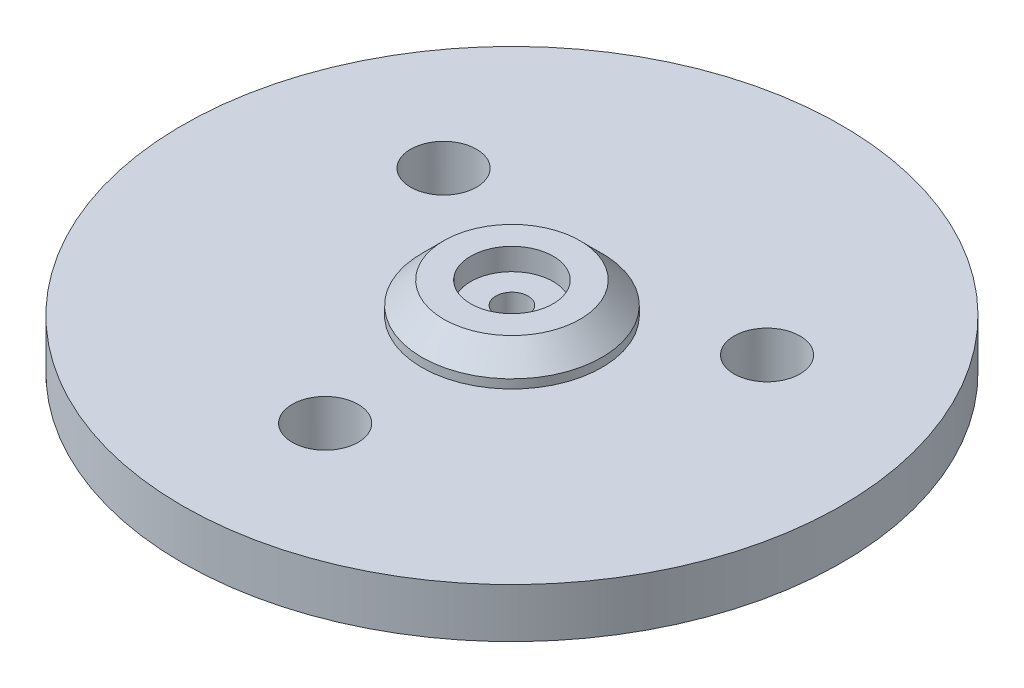
SolidWorks part; units mm, degrees
ref_plane "Спереди" through (0, 0, 0) normal (0, 0, 1) x (1, 0, 0)
ref_plane "Сверху" through (0, 0, 0) normal (0, 1, 0) x (1, 0, 0)
ref_plane "Справа" through (0, 0, 0) normal (1, 0, 0) x (0, 0, -1)
sketch "Эскиз1" plane through (0, 0, 0) normal (0, 1, 0) x (1, 0, 0)
  circle A0 centre (0, 0) radius 15
  dimension "D1" = 30
extrude "Бобышка-Вытянуть1" add sketch "Эскиз1" along normal blind 2.25
sketch "Эскиз2" plane through (0, 2.25, 0) normal (0, 1, 0) x (1, 0, 0)
  circle A0 centre (0, 0) radius 4.1
  dimension "D1" = 8.2
extrude "Бобышка-Вытянуть2" add sketch "Эскиз2" along normal blind 1.4
chamfer "Фаска1" distance 1 angle 45 1 edges at (0, 3.65, 4.1)
sketch "Эскиз3" plane through (0, 0, 0) normal (0, -1, 0) x (1, 0, 0)
  circle A0 centre (0, 0) radius 6.65
  dimension "D1" = 13.3
extrude "Бобышка-Вытянуть3" add sketch "Эскиз3" along normal blind 3.3
chamfer "Фаска2" distance 2.9 angle 45 1 edges at (0, -3.3, -6.65)
sketch "Эскиз4" plane through (0, -3.3, 0) normal (0, -1, 0) x (1, 0, 0)
  line L0 (-0.8056, 2.4344) -> (-1.7821, 1.8438)
  line L1 (1.7821, -1.8438) -> (2.4056, -0.888)
  line L2 (2.4056, -0.888) -> (2.5527, 0.2437)
  line L3 (2.5527, 0.2437) -> (2.1941, 1.3272)
  line L4 (2.1941, 1.3272) -> (1.401, 2.1477)
  line L5 (1.401, 2.1477) -> (0.3304, 2.5429)
  line L6 (0.3304, 2.5429) -> (-0.8056, 2.4344)
  line L7 (-1.7821, 1.8438) -> (-2.4056, 0.888)
  line L8 (-2.4056, 0.888) -> (-2.5527, -0.2437)
  line L9 (-2.5527, -0.2437) -> (-2.1941, -1.3272)
  line L10 (-2.1941, -1.3272) -> (-1.401, -2.1477)
  line L11 (-1.401, -2.1477) -> (-0.3304, -2.5429)
  line L12 (-0.3304, -2.5429) -> (0.8056, -2.4344)
  line L13 (0.8056, -2.4344) -> (1.7821, -1.8438)
  circle A0 centre (0, 0) radius 2.5643 construction
extrude "Вырез-Вытянуть2" cut sketch "Эскиз4" against normal blind 3
sketch "Эскиз5" plane through (0, 3.65, 0) normal (0, 1, 0) x (1, 0, 0)
  circle A0 centre (0, 0) radius 1.8776
extrude "Вырез-Вытянуть3" cut sketch "Эскиз5" against normal blind 1
sketch "Эскиз6" plane through (0, 2.65, 0) normal (0, 1, 0) x (1, 0, 0)
  circle A0 centre (0, 0) radius 0.735
extrude "Вырез-Вытянуть4" cut sketch "Эскиз6" against normal blind 10
sketch "Эскиз7" plane through (0, 0, 0) normal (0, -1, 0) x (1, 0, 0)
  line L0 (0, 0) -> (0, 8.5) construction
  line L1 (0, 0) -> (-7.3612, -4.25) construction
  line L2 (0, 0) -> (7.3612, -4.25) construction
  circle A0 centre (0, 0) radius 8.5 construction
  circle A1 centre (-7.3612, -4.25) radius 1.5
  circle A2 centre (7.3612, -4.25) radius 1.5
  circle A3 centre (0, 8.5) radius 1.5
  dimension "D1" = 17
  dimension "D4" = 3
  dimension "D5" = 3
  dimension "D6" = 3
  dimension "D2" = 120
  dimension "D3" = 120
extrude "Вырез-Вытянуть5" cut sketch "Эскиз7" against normal blind 10
